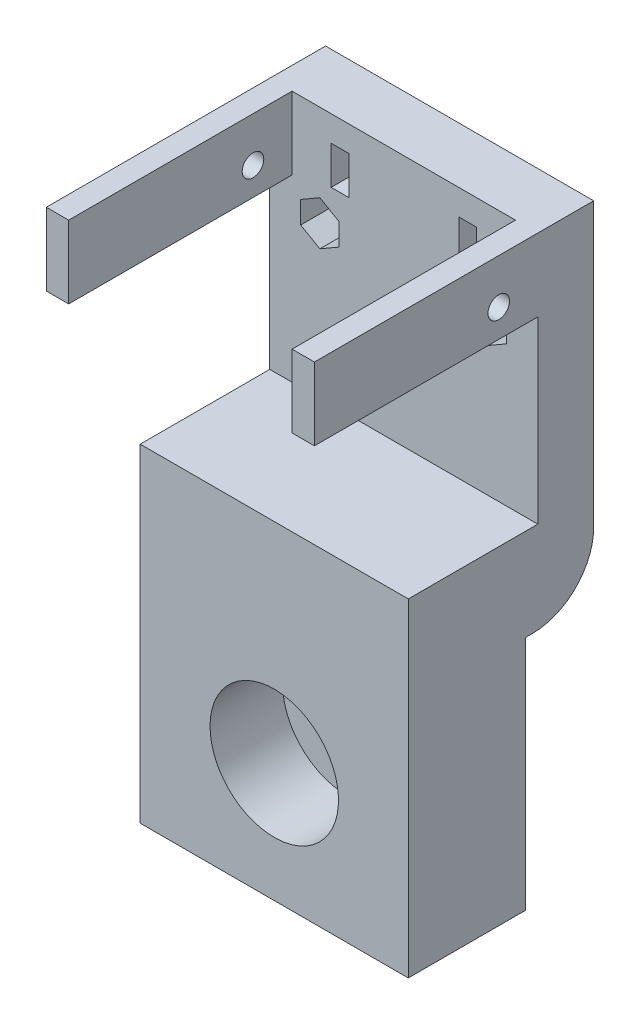
SolidWorks part; units mm, degrees
ref_plane "Front Plane" through (0, 0, 0) normal (0, 0, 1) x (1, 0, 0)
ref_plane "Top Plane" through (0, 0, 0) normal (0, 1, 0) x (1, 0, 0)
ref_plane "Right Plane" through (0, 0, 0) normal (1, 0, 0) x (0, 0, -1)
sketch "Sketch1" plane through (0, 0, 0) normal (0, 0, 1) x (1, 0, 0)
  line L1 (0, 0) -> (48, 0)
  line L2 (0, 0) -> (0, 53)
  line L3 (0, 53) -> (48, 53)
  line L4 (48, 0) -> (48, 53)
  circle A0 centre (8.975, 38) radius 1.9304
  circle A1 centre (38.975, 38) radius 1.9304
  dimension "D1" = 53
  dimension "D2" = 48
extrude "Boss-Extrude1" add sketch "Sketch1" along normal blind 10
sketch "Sketch2" plane through (0, 0, 0) normal (0, 0, -1) x (-1, 0, 0)
  line L0 (0, 53) -> (0, 0) construction
  line L1 (-48, 0) -> (0, 0)
  line L2 (-48, 0) -> (-48, -5.6163)
  line L3 (-48, -5.6163) -> (0, -5.6163)
  line L4 (0, 0) -> (0, -5.6163)
  dimension "D1" = 5.6163
extrude "Boss-Extrude2" add sketch "Sketch2" against normal blind 33.1918
sketch "Sketch4" plane through (0, 0, 10) normal (0, 0, 1) x (1, 0, 0)
  line L1 (0, 53) -> (4, 53)
  line L2 (0, 53) -> (0, 43)
  line L3 (0, 43) -> (4, 43)
  line L4 (4, 53) -> (4, 43)
  line L5 (48, 53) -> (44, 53)
  line L6 (48, 53) -> (48, 43)
  line L7 (48, 43) -> (44, 43)
  line L8 (44, 53) -> (44, 43)
  dimension "D1" = 10
  dimension "D2" = 4
extrude "Boss-Extrude4" add sketch "Sketch4" along normal blind 40
sketch "Sketch5" plane through (0, 0, 10) normal (0, 0, 1) x (1, 0, 0)
  line L0 (48, 0) -> (48, 43) construction
  line L1 (0, 0) -> (48, 0)
  line L2 (0, 0) -> (0, 10.8609)
  line L3 (0, 10.8609) -> (48, 10.8609)
  line L4 (48, 0) -> (48, 10.8609)
  dimension "D1" = 10.8609
extrude "Boss-Extrude5" add sketch "Sketch5" along normal up to surface (23.1918 mm away) up to face at (24, -2.8082, 33.1918)
sketch "Sketch6" plane through (0, -5.6163, 0) normal (0, -1, 0) x (1, 0, 0)
  line L0 (0, 0) -> (0, 28.1918) construction
  line L1 (0, 33.1918) -> (0, 0) construction
  line L2 (48, 33.1918) -> (48, 0) construction
  line L3 (0, 28.1918) -> (48, 28.1918)
  line L4 (0, 28.1918) -> (0, 33.1918)
  line L5 (0, 33.1918) -> (48, 33.1918)
  line L6 (48, 28.1918) -> (48, 33.1918)
  line L8 (48, 33.1918) -> (0, 33.1918) construction
  dimension "D2" = 5
extrude "Boss-Extrude6" add sketch "Sketch6" along normal blind 42.3
sketch "Sketch8" plane through (0, 0, 28.1918) normal (0, 0, -1) x (-1, 0, 0)
  line L0 (-24, -26.6163) -> (-24, -5.6163) construction
  line L1 (0, -5.6163) -> (-48, -5.6163) construction
  line L3 (-8.5, -42.1163) -> (-39.5, -42.1163) construction
  line L4 (-8.5, -42.1163) -> (-8.5, -11.1163) construction
  line L5 (-8.5, -11.1163) -> (-39.5, -11.1163) construction
  line L6 (-39.5, -42.1163) -> (-39.5, -11.1163) construction
  line L7 (-8.5, -42.1163) -> (-39.5, -11.1163) construction
  line L8 (-8.5, -11.1163) -> (-39.5, -42.1163) construction
  circle A0 centre (-24, -26.6163) radius 11.5
  circle A1 centre (-39.5, -11.1163) radius 2 construction
  circle A2 centre (-39.5, -42.1163) radius 2 construction
  circle A3 centre (-8.5, -11.1163) radius 2 construction
  circle A4 centre (-8.5, -42.1163) radius 2 construction
  dimension "D2" = 23
  dimension "D4" = 4
  dimension "D1" = 21
  dimension "D3" = 31
extrude "Cut-Extrude1" cut sketch "Sketch8" against normal up to next
sketch "Sketch9" plane through (48, 0, 0) normal (1, 0, 0) x (0, 0, -1)
  line L0 (0, -5.6163) -> (0, 53) construction
  line L1 (-50, 43) -> (-17, 48) construction
  line L2 (-17, 48) -> (-50, 53) construction
  circle A0 centre (-17, 48) radius 1.9304
  dimension "D1" = 3.8608
  dimension "D2" = 17
extrude "Cut-Extrude2" cut sketch "Sketch9" against normal through all
sketch "Sketch10" plane through (0, 0, 0) normal (0, 0, -1) x (-1, 0, 0)
  line L0 (-48, 53) -> (-37, 51.4163) construction
  line L1 (-37, 51.4163) -> (-33.8453, 51.4163)
  line L2 (-37, 51.4163) -> (-37, 44.5837)
  line L3 (-37, 44.5837) -> (-33.8453, 44.5837)
  line L4 (-33.8453, 51.4163) -> (-33.8453, 44.5837)
  line L5 (-14.1547, 51.4163) -> (-11, 51.4163)
  line L6 (-14.1547, 51.4163) -> (-14.1547, 44.5837)
  line L7 (-14.1547, 44.5837) -> (-11, 44.5837)
  line L8 (-11, 51.4163) -> (-11, 44.5837)
  line L9 (0, 53) -> (-11, 51.4163) construction
  line L10 (-48, 53) -> (0, 53) construction
  dimension "D1" = 3.1547
  dimension "D2" = 1.5837
  dimension "D3" = 6.8326
  dimension "D4" = 19.6906
extrude "Cut-Extrude3" cut sketch "Sketch10" against normal up to next
sketch "Sketch11" plane through (0, 0, 28.1918) normal (0, 0, -1) x (-1, 0, 0)
  line L1 (-48, -5.6163) -> (0, -5.6163)
  line L2 (-48, -5.6163) -> (-48, -47.9163)
  line L3 (-48, -47.9163) -> (0, -47.9163)
  line L4 (0, -5.6163) -> (0, -47.9163)
  circle A0 centre (-24, -26.6163) radius 11.5
  circle A1 centre (-24, -26.6163) radius 11.5 construction
extrude "Boss-Extrude7" add sketch "Sketch11" along normal blind 8
sketch "Sketch12" plane through (0, 0, 20.1918) normal (0, 0, -1) x (-1, 0, 0)
  line L1 (-48, -5.6163) -> (0, -5.6163)
  line L2 (-48, -5.6163) -> (-48, -47.9163)
  line L3 (-48, -47.9163) -> (0, -47.9163)
  line L4 (0, -5.6163) -> (0, -47.9163)
extrude "Boss-Extrude8" add sketch "Sketch12" along normal blind 8
fillet "Fillet1" radius 11 1 edges at (24, -5.6163, 0)
sketch "Sketch13" plane through (0, 53, 0) normal (0, 1, 0) x (1, 0, 0)
  line L0 (0, 0) -> (0, -50)
  line L1 (0, -50) -> (4, -50)
  line L2 (4, -50) -> (4, -10)
  line L3 (4, -10) -> (44, -10)
  line L4 (44, -10) -> (44, -50)
  line L5 (44, -50) -> (48, -50)
  line L6 (48, -50) -> (48, 0)
  line L7 (48, 0) -> (0, 0)
extrude "Boss-Extrude9" add sketch "Sketch13" along normal blind 3
sketch "Sketch14" plane through (0, 0, 10) normal (0, 0, 1) x (1, 0, 0)
  line L1 (8.975, 41.9595) -> (5.546, 39.9797)
  line L2 (5.546, 39.9797) -> (5.546, 36.0203)
  line L3 (5.546, 36.0203) -> (8.975, 34.0405)
  line L4 (8.975, 34.0405) -> (12.404, 36.0203)
  line L5 (12.404, 36.0203) -> (12.404, 39.9797)
  line L6 (12.404, 39.9797) -> (8.975, 41.9595)
  line L7 (38.975, 41.9595) -> (35.546, 39.9797)
  line L8 (35.546, 39.9797) -> (35.546, 36.0203)
  line L9 (35.546, 36.0203) -> (38.975, 34.0405)
  line L10 (38.975, 34.0405) -> (42.404, 36.0203)
  line L11 (42.404, 36.0203) -> (42.404, 39.9797)
  line L12 (42.404, 39.9797) -> (38.975, 41.9595)
  circle A0 centre (8.975, 38) radius 3.429 construction
  circle A1 centre (38.975, 38) radius 3.429 construction
  dimension "D1" = 3.9595
extrude "Cut-Extrude4" cut sketch "Sketch14" against normal blind 6
